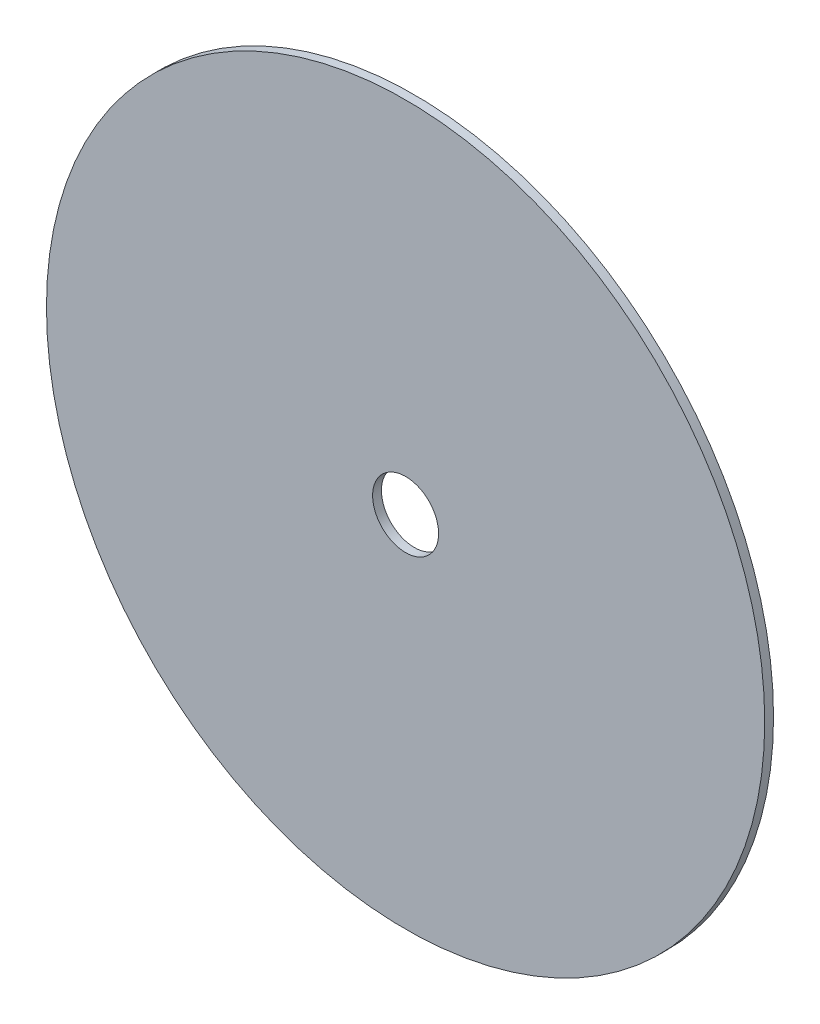
SolidWorks part; units mm, degrees
ref_plane "Front Plane" through (0, 0, 0) normal (0, 0, 1) x (1, 0, 0)
ref_plane "Top Plane" through (0, 0, 0) normal (0, 1, 0) x (1, 0, 0)
ref_plane "Right Plane" through (0, 0, 0) normal (1, 0, 0) x (0, 0, -1)
sketch "Sketch1" plane through (0, 0, 0) normal (0, 0, 1) x (1, 0, 0)
  circle A0 centre (0, 0) radius 12.25
  dimension "D1" = 24.5
extrude "Boss-Extrude1" add sketch "Sketch1" along normal blind 0.3
sketch "Sketch2" plane through (0, 0, 0.3) normal (0, 0, 1) x (1, 0, 0)
  circle A0 centre (0, 0) radius 1.125
  dimension "D1" = 2.25
extrude "Cut-Extrude1" cut sketch "Sketch2" against normal blind 0.3
